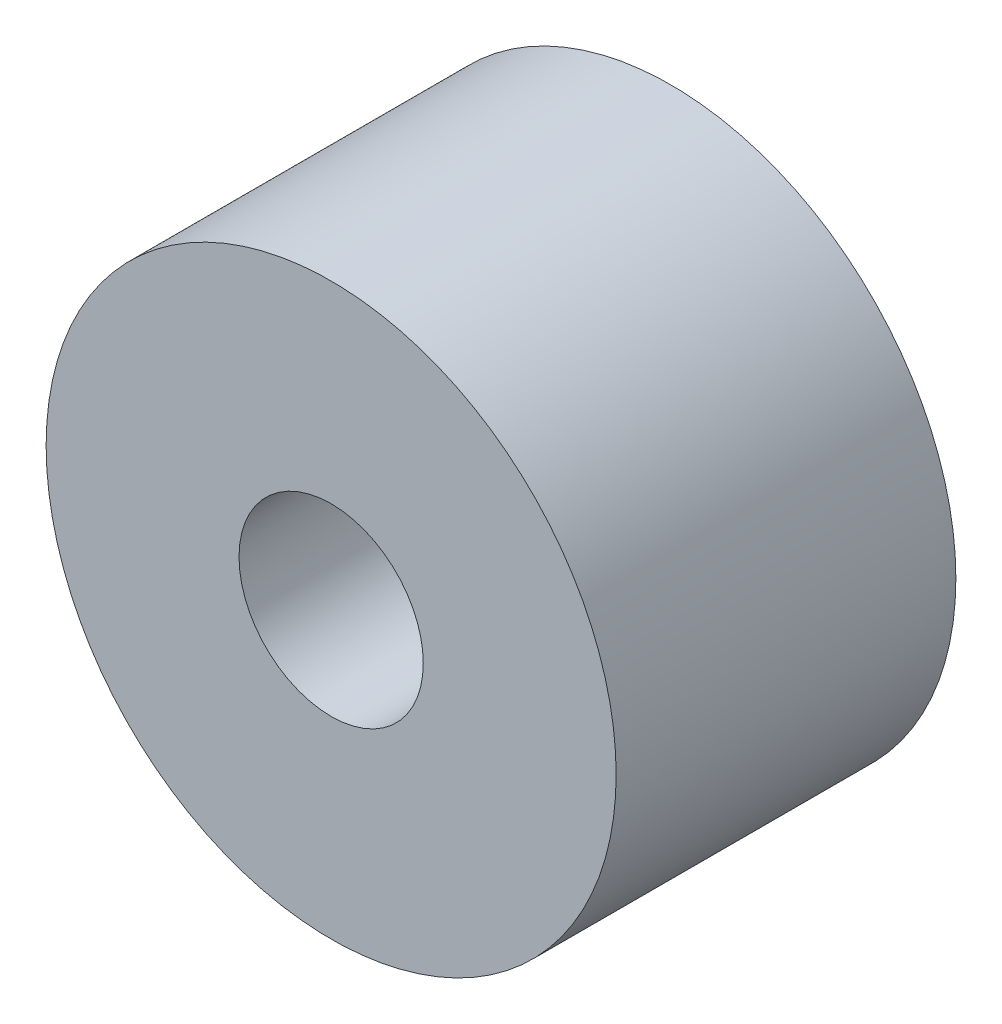
SolidWorks part; units mm, degrees
ref_plane "Plan de face" through (0, 0, 0) normal (0, 0, 1) x (1, 0, 0)
ref_plane "Plan de dessus" through (0, 0, 0) normal (0, 1, 0) x (1, 0, 0)
ref_plane "Plan de droite" through (0, 0, 0) normal (1, 0, 0) x (0, 0, -1)
sketch "Esquisse1" plane through (0, 0, 0) normal (0, 0, 1) x (1, 0, 0)
  circle A0 centre (0, 0) radius 4.95
  dimension "D1" = 9.9
extrude "Boss.-Extru.1" add sketch "Esquisse1" along normal blind 5.9
sketch "Esquisse2" plane through (0, 0, 0) normal (0, 0, -1) x (-1, 0, 0)
  circle A0 centre (0, 0) radius 1.6
  dimension "D1" = 3.2
extrude "Enlèv. mat.-Extru.1" cut sketch "Esquisse2" against normal up to surface (5.9 mm away) up to face at (4.95, 0, 5.9)
sketch "Esquisse3" plane through (0, 0, 0) normal (0, 0, -1) x (-1, 0, 0)
  line L1 (-0.9491, -3.2113) -> (2.3065, -2.4276)
  line L2 (2.3065, -2.4276) -> (3.2556, 0.7837)
  line L3 (3.2556, 0.7837) -> (0.9491, 3.2113)
  line L4 (0.9491, 3.2113) -> (-2.3065, 2.4276)
  line L5 (-2.3065, 2.4276) -> (-3.2556, -0.7837)
  line L6 (-3.2556, -0.7837) -> (-0.9491, -3.2113)
  circle A0 centre (0, 0) radius 2.9 construction
  dimension "D1" = 5.8
extrude "Enlèv. mat.-Extru.2" cut sketch "Esquisse3" against normal blind 3
